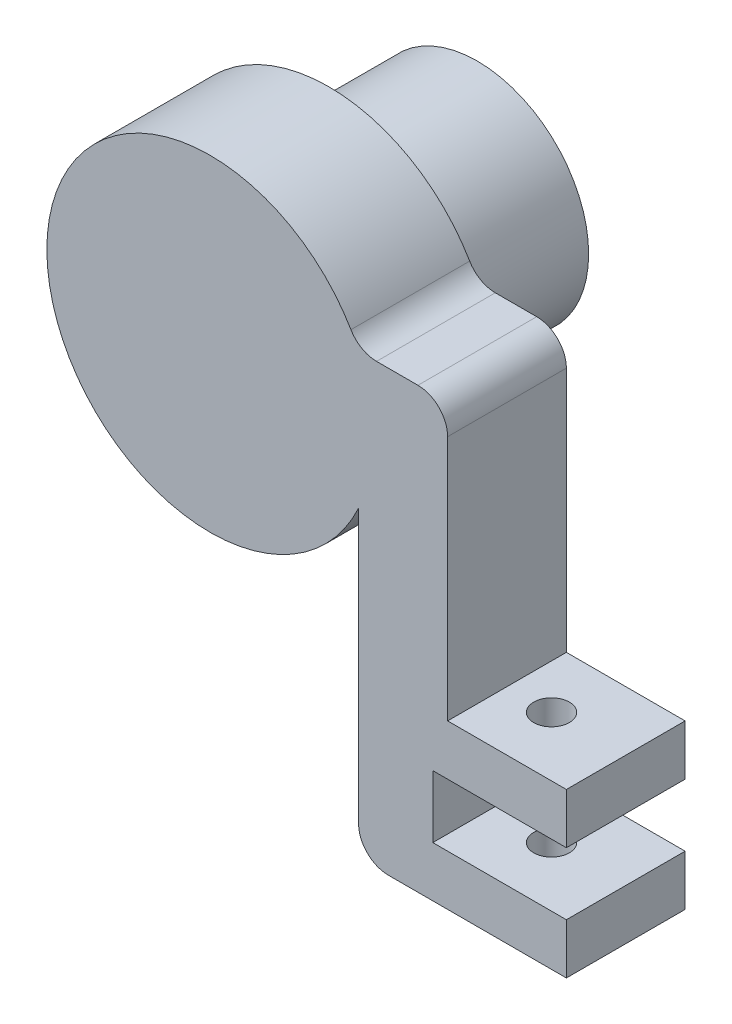
SolidWorks part; units mm, degrees
ref_plane "Plan de face" through (0, 0, 0) normal (0, 0, 1) x (1, 0, 0)
ref_plane "Plan de dessus" through (0, 0, 0) normal (0, 1, 0) x (1, 0, 0)
ref_plane "Plan de droite" through (0, 0, 0) normal (1, 0, 0) x (0, 0, -1)
sketch "Esquisse1" plane through (0, 0, 0) normal (0, 0, 1) x (1, 0, 0)
  line L1 (0, 0) -> (35, 0) construction
  line L2 (0, 0) -> (0, -36) construction
  line L3 (0, -36) -> (35, -36) construction
  line L4 (35, 0) -> (35, -36) construction
  line L5 (21, -6.4174) -> (27, -6.4174)
  line L7 (27, -6.4174) -> (27, -25)
  line L8 (35, -28.4) -> (35, -25)
  line L9 (35, -36) -> (21, -36)
  line L10 (35, -36) -> (35, -32.6)
  line L11 (35, -25) -> (27, -25)
  line L14 (21, -36) -> (21, -15.5826)
  line L17 (35, -32.6) -> (26, -32.6)
  line L19 (35, -28.4) -> (26, -28.4)
  line L20 (26, -32.6) -> (26, -28.4)
  line L21 (21, -6.4174) -> (21, -15.5826) construction
  arc A0 (21, -6.4174) -> (21, -15.5826) centre (11, -11) ccw
  point P6 (21, -11)
  point P20 (26, -30.5)
  dimension "D3" = 22
  dimension "D1" = 35
  dimension "D2" = 36
  dimension "D4" = 11
  dimension "D5" = 11
  dimension "D6" = 11
  dimension "D8" = 9
  dimension "D9" = 4.2
  dimension "D10" = 5.5
  dimension "D11" = 8
  dimension "D7" = 21
extrude "Boss.-Extru.1" add sketch "Esquisse1" along normal blind 8
sketch "Esquisse2" plane through (0, -25, 0) normal (0, 1, 0) x (1, 0, 0)
  line L0 (27, -8) -> (27, 0) construction
  line L1 (35, -8) -> (27, -8) construction
  circle A0 centre (30, -4) radius 1
  dimension "D1" = 2
  dimension "D2" = 3
  dimension "D3" = 4
extrude "Enlèv. mat.-Extru.1" cut sketch "Esquisse2" against normal up to surface (11 mm away) up to face at (28, -36, 4)
hole_wizard "Dégagement M21" positions "Esquisse3" profile "Esquisse4" hole size "M2" standard "ISO"
sketch "Esquisse3" plane through (0, -25, 0) normal (0, 1, 0) x (1, 0, 0)
  point P0 (30, -4)
sketch "Esquisse4" plane through (30, -25, 4) normal (1, 0, 0) x (0, 0, 1)
  line L0 (0, 0) -> (0, 11.721)
  line L1 (0, 11.721) -> (1.2, 11)
  line L2 (1.2, 11) -> (1.2, 0)
  line L5 (1.2, 0) -> (0, 0)
  line L10 (0, 11.721) -> (-1.2, 11) construction
  line L11 (0, -6.35) -> (0, 107.95) construction
  dimension "Diamètre du perçage" = 2.4
  dimension "Profondeur du perçage" = 11
  dimension "Angle de pointe" = 118
fillet "Congé1" radius 2 3 edges at (21, -36, 4) (21, -6.4174, 4) (27, -6.4174, 4)
sketch "Esquisse5" plane through (0, 0, 8) normal (0, 0, 1) x (1, 0, 0)
  circle A0 centre (11, -11) radius 7.5
  dimension "D1" = 15
extrude "Boss.-Extru.2" [suppressed] add sketch "Esquisse5" along normal blind 10
sketch "Esquisse6" plane through (0, 0, 0) normal (0, 0, -1) x (-1, 0, 0)
  circle A0 centre (-11, -11) radius 7.5
  dimension "D1" = 15
extrude "Boss.-Extru.3" add sketch "Esquisse6" along normal blind 10
equation "\"D4@Esquisse1\"=\"D3@Esquisse1\"/2"
equation "\"D5@Esquisse1\"=\"D3@Esquisse1\"/2"
equation "\"D10@Esquisse1\"=\"D6@Esquisse1\"/2"
